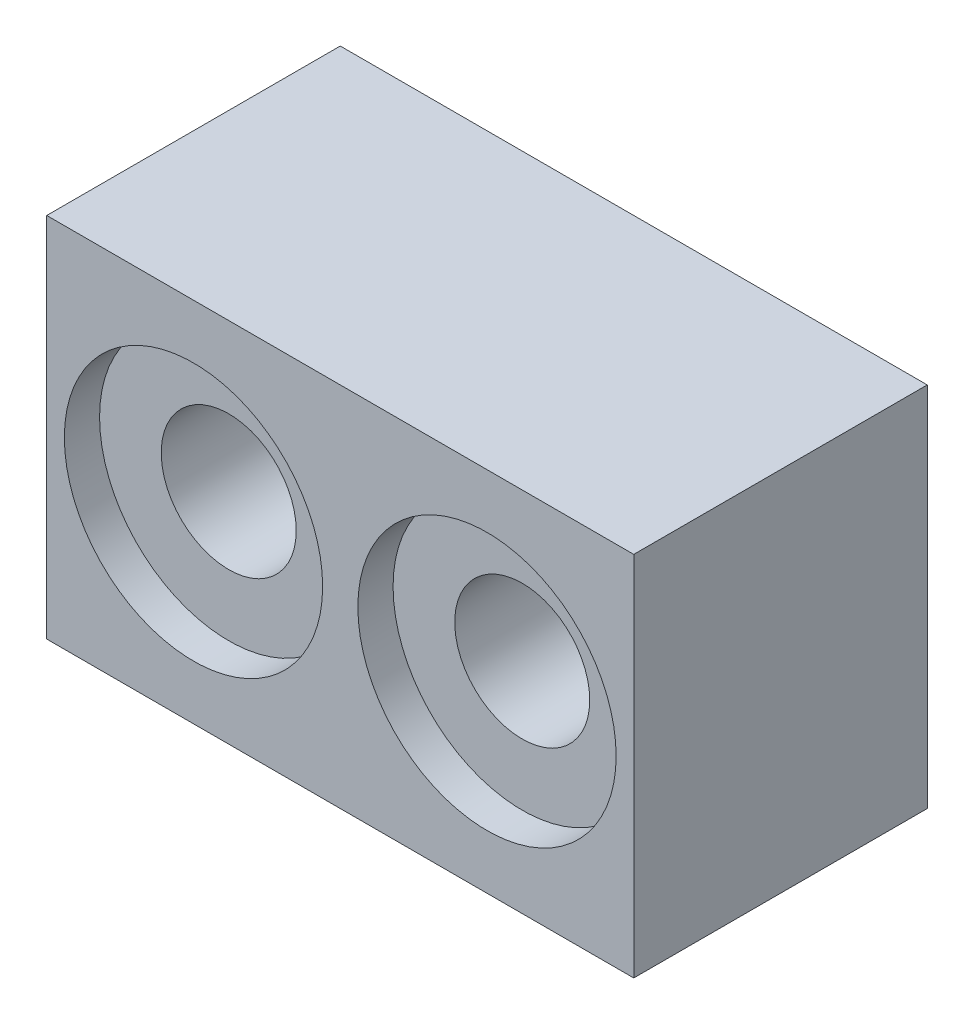
SolidWorks part; units mm, degrees
material "Chrome Stainless Steel"
ref_plane "Front Plane" through (0, 0, 0) normal (0, 0, 1) x (1, 0, 0)
ref_plane "Top Plane" through (0, 0, 0) normal (0, 1, 0) x (1, 0, 0)
ref_plane "Right Plane" through (0, 0, 0) normal (1, 0, 0) x (0, 0, -1)
sketch "Sketch1" plane through (0, 0, 0) normal (0, 0, 1) x (1, 0, 0)
  line L1 (0, 0) -> (12.7, 0)
  line L2 (0, 0) -> (0, 7.9375)
  line L3 (0, 7.9375) -> (12.7, 7.9375)
  line L4 (12.7, 0) -> (12.7, 7.9375)
  dimension "D1" = 12.7
  dimension "D2" = 7.9375
extrude "Boss-Extrude1" add sketch "Sketch1" along normal blind 6.35
sketch "Sketch2" plane through (0, 0, 6.35) normal (0, 0, 1) x (1, 0, 0)
  line L0 (0, 3.9688) -> (12.7, 3.9688) construction
  line L1 (0, 7.9375) -> (0, 0) construction
  line L2 (12.7, 0) -> (12.7, 7.9375) construction
  line L3 (6.35, 7.9375) -> (6.35, 0) construction
  line L4 (12.7, 7.9375) -> (0, 7.9375) construction
  line L5 (0, 0) -> (12.7, 0) construction
  circle A0 centre (3.175, 3.9688) radius 2.794
  circle A1 centre (9.525, 3.9688) radius 2.794
  point P12 (3.175, 3.9688)
  point P13 (9.525, 3.9688)
  dimension "D2" = 5.588
  dimension "D3" = 5.588
  dimension "D1" = 6.35
extrude "Cut-Extrude1" cut sketch "Sketch2" against normal blind 0.762
sketch "Sketch3" plane through (0, 0, 5.588) normal (0, 0, 1) x (1, 0, 0)
  circle A0 centre (3.175, 3.9688) radius 1.4605
  circle A1 centre (9.525, 3.9688) radius 1.4605
  dimension "D1" = 2.921
  dimension "D2" = 2.921
extrude "Cut-Extrude2" cut sketch "Sketch3" against normal through all
